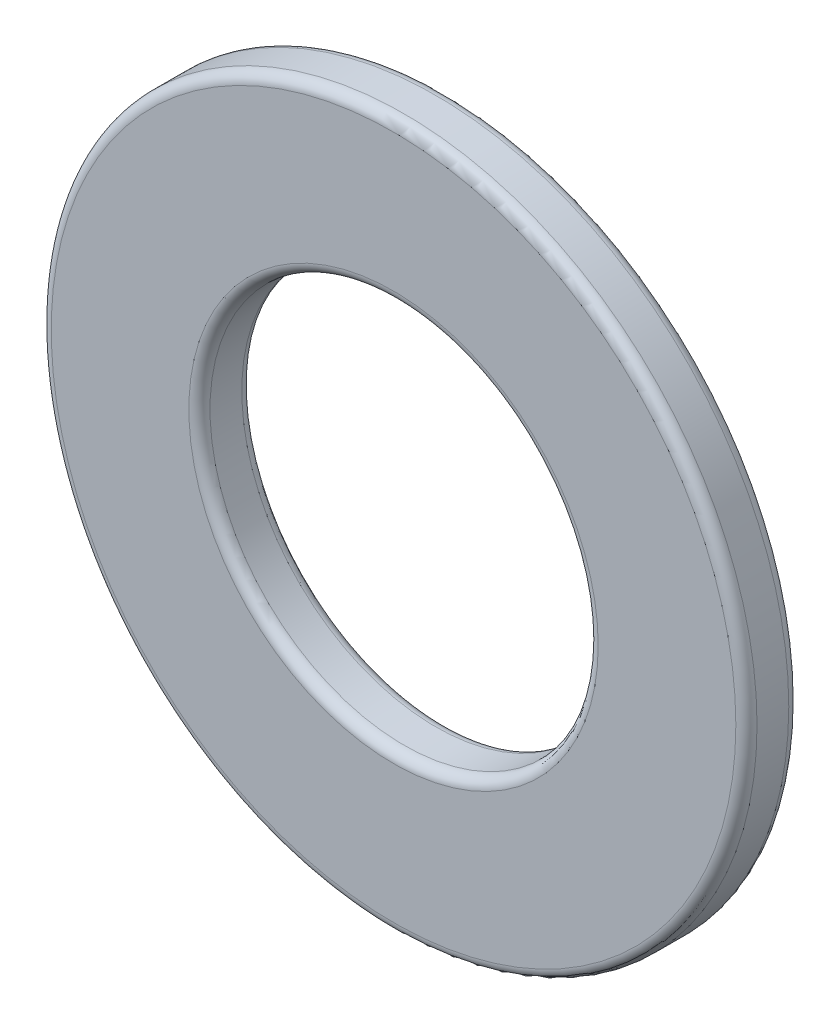
SolidWorks part; units mm, degrees
material "AISI 304"
ref_plane "Front Plane" through (0, 0, 0) normal (0, 0, 1) x (1, 0, 0)
ref_plane "Top Plane" through (0, 0, 0) normal (0, 1, 0) x (1, 0, 0)
ref_plane "Right Plane" through (0, 0, 0) normal (1, 0, 0) x (0, 0, -1)
sketch "Sketch1" plane through (0, 0, 0) normal (0, 0, 1) x (1, 0, 0)
  line L0 (0, 0) -> (1.1, 0) construction
  line L1 (0, -55) -> (0, 55) construction
  circle A0 centre (0, 0) radius 2
  circle A1 centre (0, 0) radius 1.1
  dimension "D1" = 90
  dimension "OD" = 4
  dimension "ID" = 2.2
sketch "Sketch2" plane through (0, 0, 0) normal (1, 0, 0) x (0, 0, -1)
  line L0 (-0.15, 2) -> (0.15, 2) construction
  point P5 (0, 2)
  dimension "Thickness" = 0.3
sketch "Sketch3" plane through (0, 0, 0) normal (0, 0, 1) x (1, 0, 0)
  circle A0 centre (0, 0) radius 1.1 construction
  circle A1 centre (0, 0) radius 2 construction
  circle A2 centre (0, 0) radius 1.1
  circle A3 centre (0, 0) radius 2
extrude "Boss-Extrude1" add sketch "Sketch3" against normal up to vertex (0.15 mm away) from vertex at 0.15 starting at point (0, 2, 0.15)
fillet "Fillet1" radius 0.06 4 edges at (2, 0, 0.15) (1.1, 0, 0.15) (2, 0, -0.15) (1.1, 0, -0.15)
